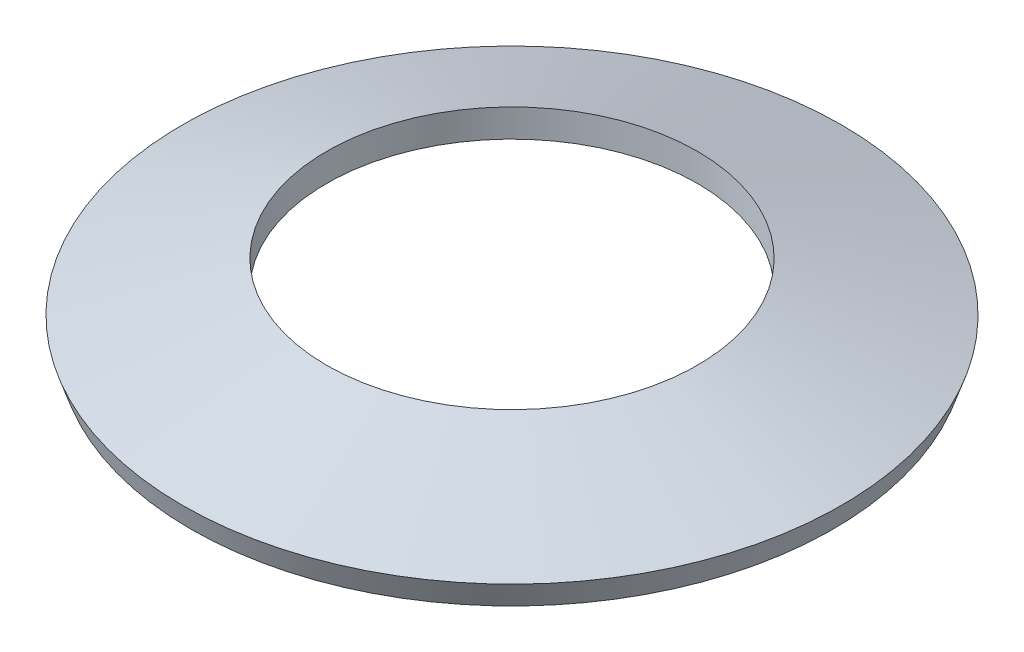
SolidWorks part; units mm, degrees
ref_plane "Plan de face" through (0, 0, 0) normal (0, 0, 1) x (1, 0, 0)
ref_plane "Plan de dessus" through (0, 0, 0) normal (0, 1, 0) x (1, 0, 0)
ref_plane "Plan de droite" through (0, 0, 0) normal (1, 0, 0) x (0, 0, -1)
ref_plane "Plan1" through (0, 0, 10.4) normal (0, 0, -1) x (-1, 0, 0)
sketch "Esquisse1" plane through (0, 0, 10.4) normal (0, 0, -1) x (-1, 0, 0)
  line L0 (-44.9752, -18.5314) -> (-44.7685, -19.1371)
  line L1 (-44.7685, -19.1371) -> (-41.4752, -18.0134)
  line L2 (-41.4752, -18.0134) -> (-41.4752, -17.3371)
  line L3 (-41.4752, -17.3371) -> (-44.9752, -18.5314)
  line L4 (-36.9752, -19.1606) -> (-36.9752, -16.6071) construction
  dimension "D1" = 0.64
  dimension "D2" = 1.8
  dimension "D3" = 16
  dimension "D4" = 9
revolve "Révolution1" add sketch "Esquisse1" angle 360 about L4
